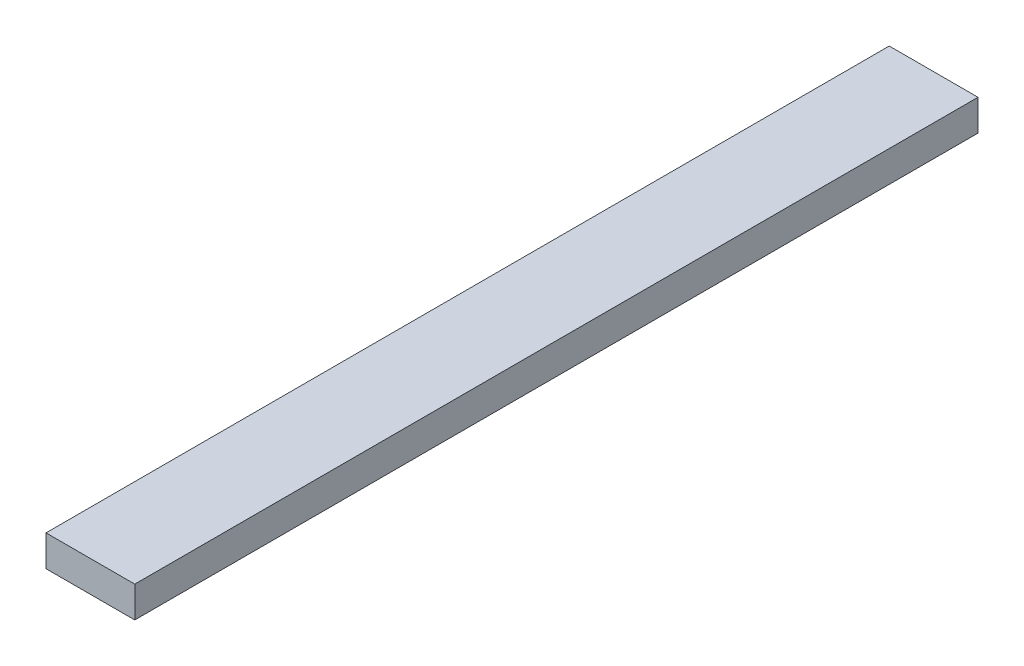
SolidWorks part; units mm, degrees
material "3.0205 (EN-AW 1200)"
ref_plane "Alzado" through (0, 0, 0) normal (0, 0, 1) x (1, 0, 0)
ref_plane "Planta" through (0, 0, 0) normal (0, 1, 0) x (1, 0, 0)
ref_plane "Vista lateral" through (0, 0, 0) normal (1, 0, 0) x (0, 0, -1)
sketch "Croquis1" plane through (0, 0, 0) normal (0, 1, 0) x (1, 0, 0)
  line L1 (0, 0) -> (20, 0)
  line L2 (0, 0) -> (0, 190)
  line L3 (0, 190) -> (20, 190)
  line L4 (20, 0) -> (20, 190)
  line L6 (0, 142.5) -> (20, 142.5)
  dimension "D1" = 190
  dimension "D2" = 20
  dimension "D3" = 47.5
extrude "Saliente-Extruir1" add sketch "Croquis1" along normal blind 7
